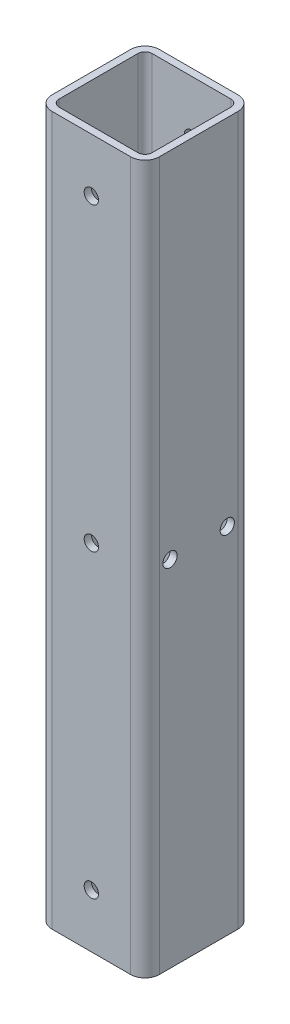
SolidWorks part; units mm, degrees
material "AISI 1010 钢，热轧条材"
ref_plane "前视基准面" through (0, 0, 0) normal (0, 0, 1) x (1, 0, 0)
ref_plane "上视基准面" through (0, 0, 0) normal (0, 1, 0) x (1, 0, 0)
ref_plane "右视基准面" through (0, 0, 0) normal (1, 0, 0) x (0, 0, -1)
sketch "草图1" plane through (0, 0, 0) normal (0, 1, 0) x (1, 0, 0)
  line L0 (-11, -13) -> (11, -13)
  line L1 (-11, -15) -> (11, -15)
  line L2 (-15, -11) -> (-15, 11)
  line L3 (-11, 15) -> (11, 15)
  line L4 (15, -11) -> (15, 11)
  line L5 (13, -11) -> (13, 11)
  line L6 (-11, 13) -> (11, 13)
  line L7 (-13, -11) -> (-13, 11)
  arc A0 (-11, -15) -> (-15, -11) centre (-11, -11) cw
  arc A1 (11, -15) -> (15, -11) centre (11, -11) ccw
  arc A2 (11, 15) -> (15, 11) centre (11, 11) cw
  arc A3 (-15, 11) -> (-11, 15) centre (-11, 11) cw
  arc A4 (11, -13) -> (13, -11) centre (11, -11) ccw
  arc A5 (11, 13) -> (13, 11) centre (11, 11) cw
  arc A6 (-13, 11) -> (-11, 13) centre (-11, 11) cw
  arc A7 (-11, -13) -> (-13, -11) centre (-11, -11) cw
extrude "凸台-拉伸1" add sketch "草图1" along normal mid plane 198
sketch "草图2" plane through (0, 0, 0) normal (1, 0, 0) x (0, 0, -1)
  line L0 (-15, 0) -> (15, 0) construction
  line L1 (-15, 99) -> (-15, -99) construction
  line L2 (15, 99) -> (15, -99) construction
  circle A0 centre (8, 0) radius 2
  circle A1 centre (-8, 0) radius 2
  dimension "D1" = 4
  dimension "D2" = 16
  dimension "D3" = 8
extrude "切除-拉伸1" cut sketch "草图2" against normal through all both and the other way through all
sketch "草图3" plane through (0, 0, 0) normal (0, 0, 1) x (1, 0, 0)
  line L0 (-15, 0) -> (14.6751, 0) construction
  line L1 (-15, 99) -> (-15, -99) construction
  line L2 (-11, 99) -> (11, 99) construction
  circle A0 centre (0, 84) radius 2
  circle A1 centre (0, 0) radius 2
  circle A2 centre (0, -84) radius 2
  dimension "D1" = 4
  dimension "D2" = 15
extrude "切除-拉伸2" cut sketch "草图3" against normal through all both and the other way through all
